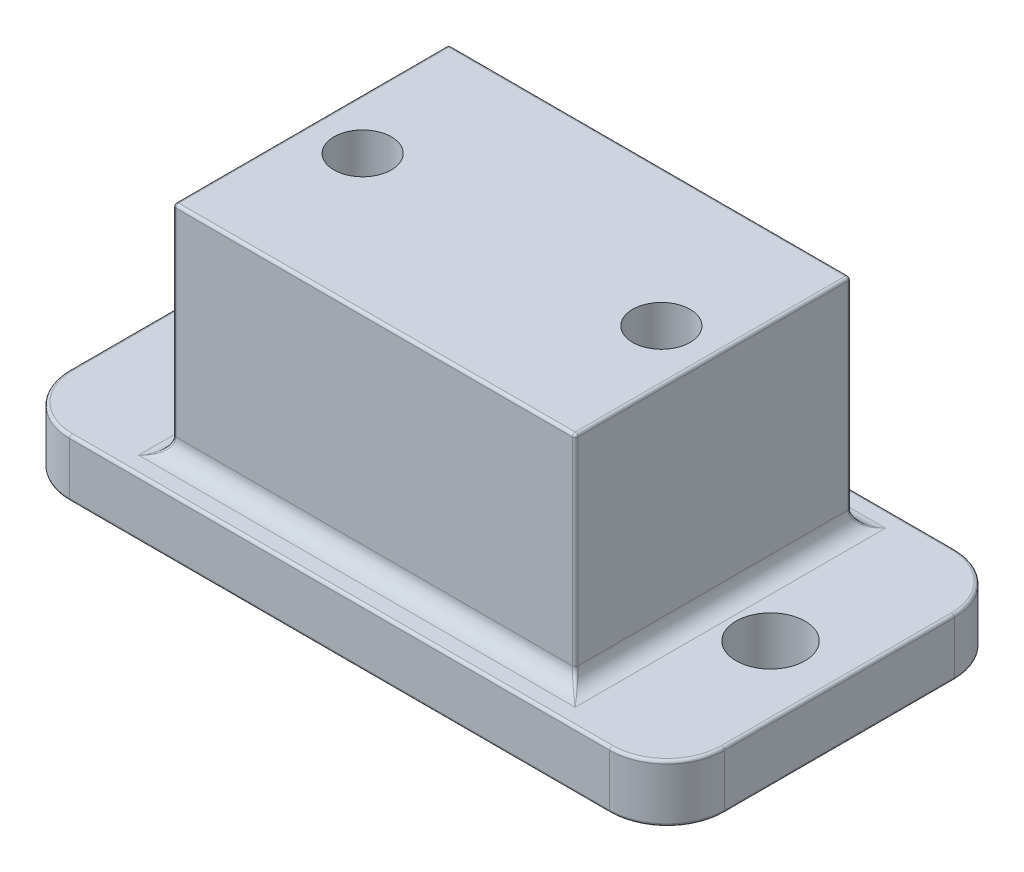
SolidWorks part; units mm, degrees
ref_plane "Front Plane" through (0, 0, 0) normal (0, 0, 1) x (1, 0, 0)
ref_plane "Top Plane" through (0, 0, 0) normal (0, 1, 0) x (1, 0, 0)
ref_plane "Right Plane" through (0, 0, 0) normal (1, 0, 0) x (0, 0, -1)
sketch "Sketch1" plane through (0, 0, 0) normal (0, 1, 0) x (1, 0, 0)
  line L1 (23.5, -15) -> (-23.5, -15)
  line L2 (28.5, -10) -> (28.5, 10)
  line L3 (23.5, 15) -> (-23.5, 15)
  line L4 (-28.5, -10) -> (-28.5, 10)
  line L5 (28.5, -15) -> (-28.5, 15) construction
  line L6 (28.5, 15) -> (-28.5, -15) construction
  arc A0 (-23.5, -15) -> (-28.5, -10) centre (-23.5, -10) cw
  arc A1 (23.5, -15) -> (28.5, -10) centre (23.5, -10) ccw
  arc A2 (28.5, 10) -> (23.5, 15) centre (23.5, 10) ccw
  arc A3 (-23.5, 15) -> (-28.5, 10) centre (-23.5, 10) ccw
  circle A4 centre (-22.5, 0) radius 3
  circle A5 centre (22.5, 0) radius 3
  point P0 (0, 0)
  point P22 (0, 0)
  point P23 (0, 0)
  dimension "D3" = 5
  dimension "D4" = 6
  dimension "D5" = 6
  dimension "D1" = 30
  dimension "D2" = 57
  dimension "D6" = 6
  dimension "D7" = 6
extrude "Boss-Extrude1" add sketch "Sketch1" along normal blind 5
sketch "Sketch2" plane through (0, 0, 0) normal (0, 0, 1) x (1, 0, 0)
  line L0 (-23.5, 5) -> (23.5, 5) construction
  line L1 (17.5, 5) -> (-17.5, 5)
  line L2 (17.5, 5) -> (17.5, 24)
  line L3 (17.5, 24) -> (-17.5, 24)
  line L4 (-17.5, 5) -> (-17.5, 24)
  line L5 (17.5, 5) -> (-17.5, 24) construction
  line L6 (17.5, 24) -> (-17.5, 5) construction
  point P0 (0, 14.5)
  point P7 (0, 0)
  dimension "D1" = 19
  dimension "D2" = 35
extrude "Boss-Extrude2" add sketch "Sketch2" along normal mid plane 24
sketch "Sketch3" plane through (0, 24, 0) normal (0, 1, 0) x (1, 0, 0)
  line L0 (-17.5, -12) -> (-17.5, 12) construction
  line L1 (17.5, -12) -> (17.5, 12) construction
  circle A0 centre (-13, 0) radius 2.5
  circle A1 centre (13, 0) radius 2.5
  point P8 (0, 0)
  dimension "D1" = 5
  dimension "D4" = 5
  dimension "D2" = 4.5
  dimension "D3" = 4.5
extrude "Cut-Extrude1" cut sketch "Sketch3" against normal blind 13
fillet "Fillet1" radius 1.5 4 edges at (-17.5, 5, 0) (0, 5, -12) (17.5, 5, 0) (0, 5, 12)
fillet "Fillet2" radius 0.25 16 edges at (-27.0355, 5, -13.5355) (0, 5, -15) (27.0355, 5, -13.5355) (28.5, 5, 0) (27.0355, 5, 13.5355) (0, 5, 15) (-27.0355, 5, 13.5355) (-27.0355, 0, -13.5355) (0, 0, -15) (27.0355, 0, -13.5355) (28.5, 0, 0) (27.0355, 0, 13.5355) (0, 0, 15) (-27.0355, 0, 13.5355) (-28.5, 5, 0) (-28.5, 0, 0)
fillet "Fillet3" radius 0.25 12 edges at (-17.9393, 5.4393, -12.4393) (17.9393, 5.4393, -12.4393) (17.9393, 5.4393, 12.4393) (-17.9393, 5.4393, 12.4393) (-17.5, 24, 0) (0, 24, -12) (-17.5, 15.25, -12) (17.5, 24, 0) (17.5, 15.25, -12) (0, 24, 12) (17.5, 15.25, 12) (-17.5, 15.25, 12)
